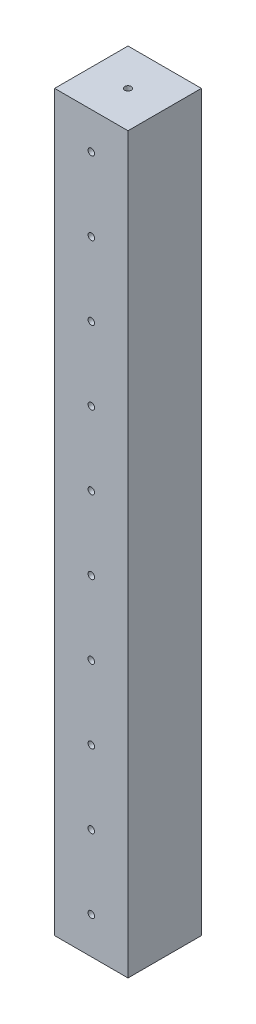
SolidWorks part; units mm, degrees
ref_plane "Front Plane" through (0, 0, 0) normal (0, 0, 1) x (1, 0, 0)
ref_plane "Top Plane" through (0, 0, 0) normal (0, 1, 0) x (1, 0, 0)
ref_plane "Right Plane" through (0, 0, 0) normal (1, 0, 0) x (0, 0, -1)
sketch "Sketch1" plane through (0, 0, 0) normal (0, 1, 0) x (1, 0, 0)
  line L1 (0, 0) -> (25.4, 0)
  line L2 (0, 0) -> (0, -25.4)
  line L3 (0, -25.4) -> (25.4, -25.4)
  line L4 (25.4, 0) -> (25.4, -25.4)
  dimension "D1" = 25.4
extrude "Boss-Extrude1" add sketch "Sketch1" along normal blind 254
hole_wizard "#4-40 Tapped Hole1" positions "3DSketch1" profile "Sketch2" tap size "#4-40" standard "ANSI Inch"
sketch3d "3DSketch1"
  line L0 (25.4, 254, 25.4) -> (25.4, 254, 0) construction
  line L1 (25.4, 254, 0) -> (0, 254, 0) construction
  point P0 (12.7, 254, 12.7)
  point P2 (12.7, 0, 12.7)
  point P5 (0, 0, 0)
  dimension "D1" = 12.7
  dimension "D2" = 12.7
sketch "Sketch2" plane through (12.7, 254, 12.7) normal (1, 0, 0) x (0, 0, 1)
  line L0 (0, 0) -> (0, 8.2792)
  line L1 (0, 8.2792) -> (1.1303, 7.6)
  line L2 (1.1303, 7.6) -> (1.1303, 0)
  line L5 (1.1303, 0) -> (0, 0)
  line L10 (0, 8.2792) -> (-1.1303, 7.6) construction
  line L11 (0, -6.35) -> (0, 107.95) construction
  dimension "Tap Drill Dia." = 2.2606
  dimension "Tap Drill Depth" = 7.6
  dimension "Drill Angle" = 118
cosmetic thread "Hole Thread1"
cosmetic thread "Hole Thread2"
hole_wizard "#4-40 Tapped Hole2" positions "3DSketch2" profile "Sketch3" tap size "#4-40" standard "ANSI Inch" end condition through all
sketch3d "3DSketch2"
  line L0 (0, 254, 0) -> (0, 0, 0) construction
  line L1 (25.4, 254, 0) -> (0, 254, 0) construction
  point P0 (12.7, 241.3, 0)
  dimension "D1" = 12.7
  dimension "D2" = 12.7
sketch "Sketch3" plane through (12.7, 241.3, 0) normal (1, 0, 0) x (0, 1, 0)
  line L0 (0, 0) -> (0, 25.4)
  line L1 (0, 25.4) -> (1.1303, 25.4)
  line L2 (1.1303, 25.4) -> (1.1303, 0)
  line L5 (1.1303, 0) -> (0, 0)
  line L11 (0, -6.35) -> (0, 107.95) construction
  dimension "Thru Tap Drill Dia." = 2.2606
  dimension "Thru Tap Drill Depth" = 25.4
cosmetic thread "Hole Thread3" parameters "D2"=2.8448
pattern_linear "LPattern1" count 10 spacing 25.4 along (0, -1, 0) of "#4-40 Tapped Hole2"
cosmetic thread "Hole Thread4"
cosmetic thread "Hole Thread5"
cosmetic thread "Hole Thread6"
cosmetic thread "Hole Thread7"
cosmetic thread "Hole Thread8"
cosmetic thread "Hole Thread9"
cosmetic thread "Hole Thread10"
cosmetic thread "Hole Thread11"
cosmetic thread "Hole Thread12"
